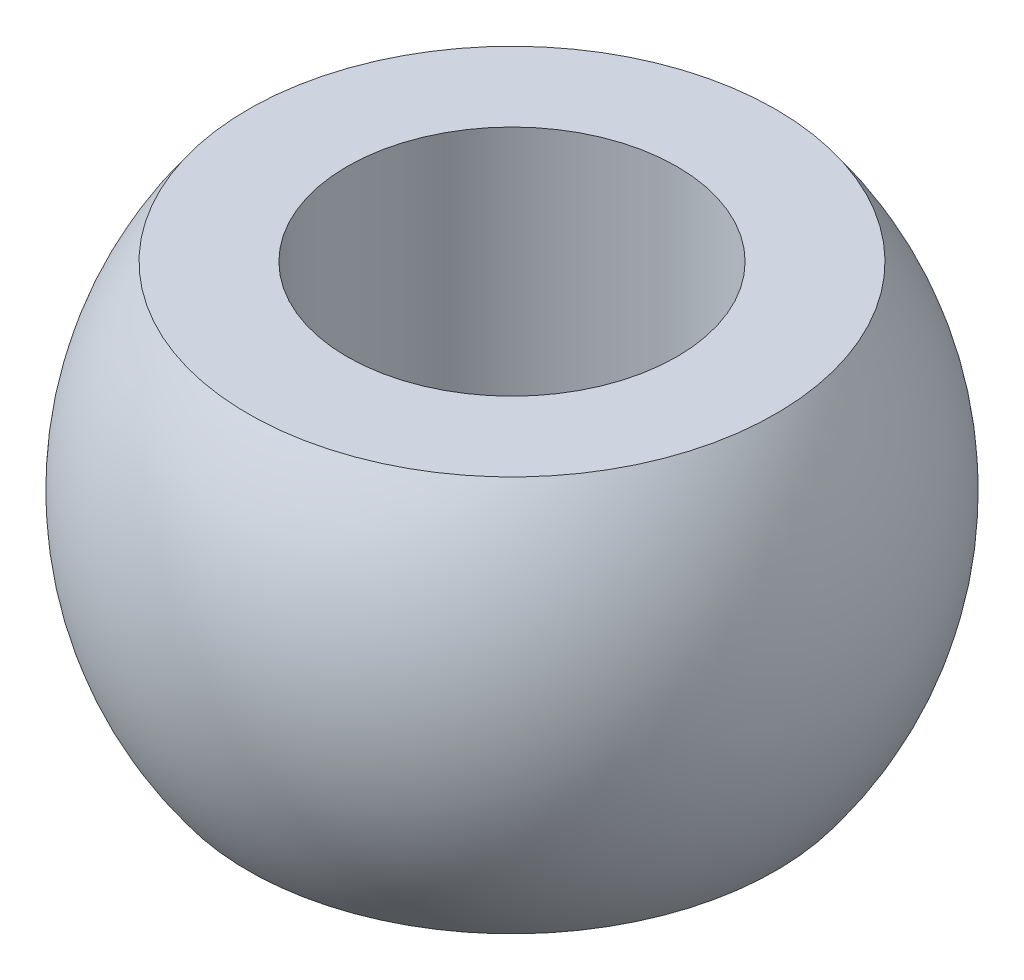
SolidWorks part; units mm, degrees
ref_plane "Alzado" through (0, 0, 0) normal (0, 0, 1) x (1, 0, 0)
ref_plane "Planta" through (0, 0, 0) normal (0, 1, 0) x (1, 0, 0)
ref_plane "Vista lateral" through (0, 0, 0) normal (1, 0, 0) x (0, 0, -1)
sketch "Croquis1" plane through (0, 0, 0) normal (1, 0, 0) x (0, 0, -1)
  line L0 (0, 0) -> (7.9375, 0) construction
  line L1 (6.35, 4.7625) -> (0, 4.7625) construction
  line L2 (0, -4.7625) -> (6.35, -4.7625) construction
  line L3 (0, -4.7625) -> (0, 0) construction
  line L4 (0, 4.7625) -> (0, -4.7625) construction
  line L5 (3.9688, 4.7625) -> (3.9688, -4.7625)
  line L6 (3.9688, -4.7625) -> (6.35, -4.7625)
  line L7 (3.9688, 4.7625) -> (6.35, 4.7625)
  arc A1 (6.35, -4.7625) -> (6.35, 4.7625) centre (0, 0) ccw
  dimension "D1" = 3.9688
  dimension "D2" = 9.525
  dimension "D3" = 4.7625
  dimension "D4" = 7.9375
revolve "Revolución1" add sketch "Croquis1" angle 360 about L3
